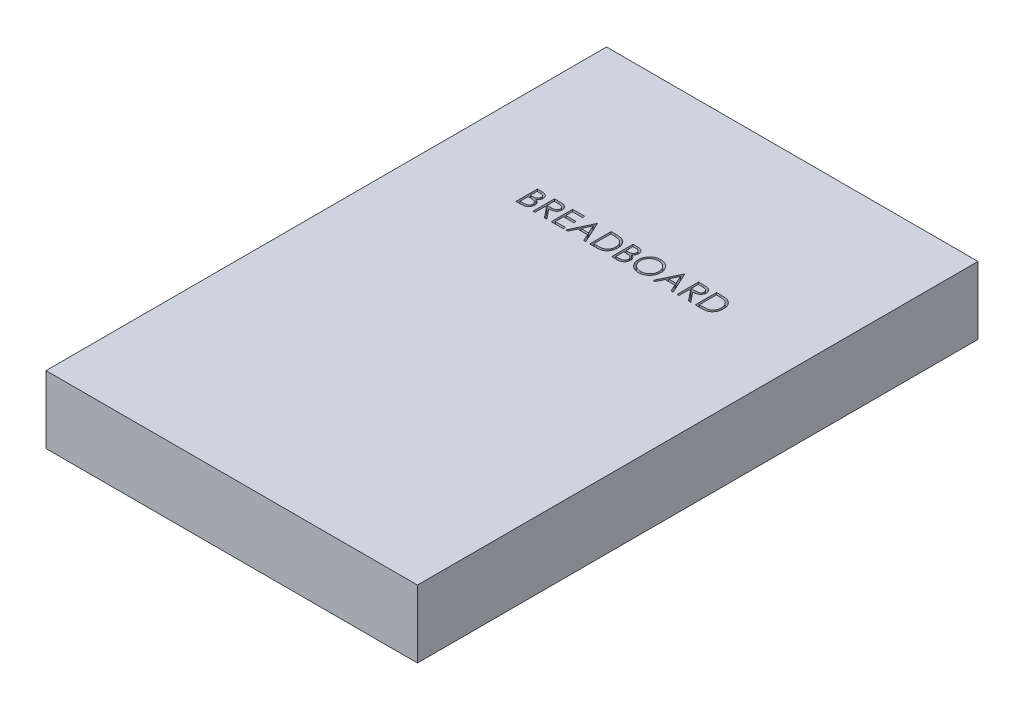
SolidWorks part; units mm, degrees
ref_plane "Front Plane" through (0, 0, 0) normal (0, 0, 1) x (1, 0, 0)
ref_plane "Top Plane" through (0, 0, 0) normal (0, 1, 0) x (1, 0, 0)
ref_plane "Right Plane" through (0, 0, 0) normal (1, 0, 0) x (0, 0, -1)
sketch "Sketch1" plane through (0, 0, 0) normal (0, 1, 0) x (1, 0, 0)
  line L1 (-27.5, -41.5) -> (27.5, -41.5)
  line L2 (-27.5, -41.5) -> (-27.5, 41.5)
  line L3 (-27.5, 41.5) -> (27.5, 41.5)
  line L4 (27.5, -41.5) -> (27.5, 41.5)
  line L5 (-27.5, -41.5) -> (27.5, 41.5) construction
  line L6 (-27.5, 41.5) -> (27.5, -41.5) construction
  point P0 (0, 0)
  dimension "D1" = 55
  dimension "D2" = 83
extrude "Boss-Extrude1" add sketch "Sketch1" along normal blind 10
sketch "Sketch2" plane through (0, 10, 0) normal (0, 1, 0) x (1, 0, 0)
  text T0 "BREADBOARD"
extrude "Cut-Extrude1" cut sketch "Sketch2" against normal blind 1
